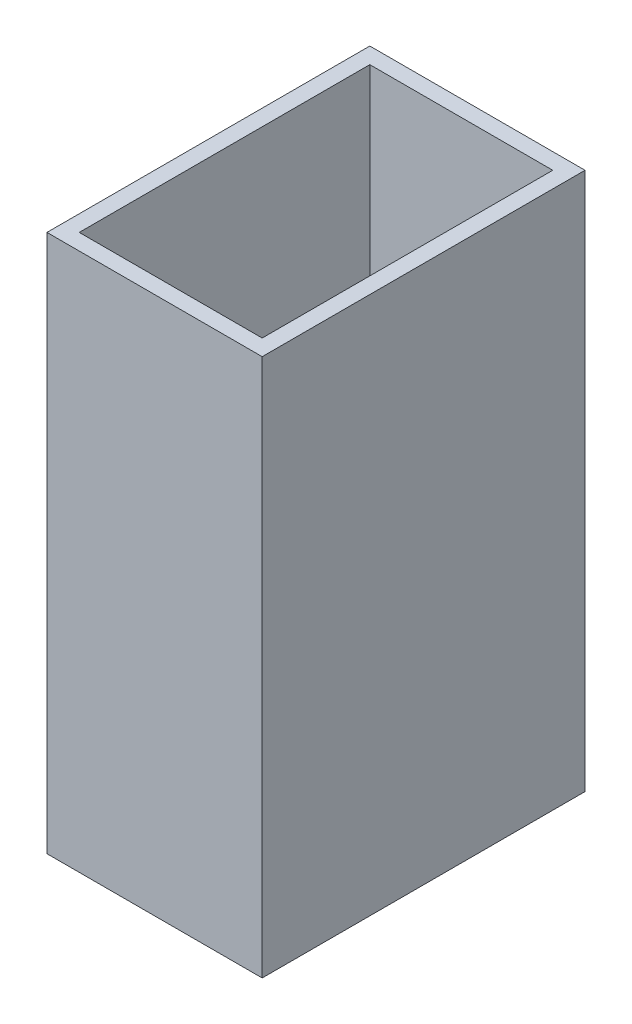
SolidWorks part; units mm, degrees
ref_plane "Front Plane" through (0, 0, 0) normal (0, 0, 1) x (1, 0, 0)
ref_plane "Top Plane" through (0, 0, 0) normal (0, 1, 0) x (1, 0, 0)
ref_plane "Right Plane" through (0, 0, 0) normal (1, 0, 0) x (0, 0, -1)
sketch "Sketch1" plane through (0, 0, 0) normal (0, 1, 0) x (1, 0, 0)
  line L1 (0, 0) -> (40, 0)
  line L2 (0, 0) -> (0, -60)
  line L3 (0, -60) -> (40, -60)
  line L4 (40, 0) -> (40, -60)
  dimension "D1" = 40
  dimension "D2" = 60
extrude "Boss-Extrude1" add sketch "Sketch1" along normal blind 100
sketch "Sketch2" plane through (0, 100, 0) normal (0, 1, 0) x (1, 0, 0)
  line L8 (3, -3) -> (3, -57)
  line L9 (3, -57) -> (37, -57)
  line L10 (37, -57) -> (37, -3)
  line L11 (37, -3) -> (3, -3)
  line L12 (3, -3) -> (3, -57)
  line L13 (3, -57) -> (37, -57)
  line L14 (37, -57) -> (37, -3)
  line L15 (37, -3) -> (3, -3)
  dimension "D1" = 3
extrude "Cut-Extrude1" cut sketch "Sketch2" against normal offset from surface 10 and the other way through all up to face at (20, 0, 30)
sketch "Sketch3" plane through (0, 0, 0) normal (0, -1, 0) x (1, 0, 0)
  line L0 (20, 60) -> (20, 0) construction
  line L1 (0, 60) -> (40, 60) construction
  line L2 (40, 0) -> (0, 0) construction
  line L3 (40, 30) -> (0, 30) construction
  line L4 (40, 60) -> (40, 0) construction
  line L5 (0, 0) -> (0, 60) construction
  circle A0 centre (7.3, 47.78) radius 2.5
  circle A1 centre (32.7, 47.78) radius 2.5
  circle A2 centre (32.7, 12.22) radius 2.5
  circle A3 centre (7.3, 12.22) radius 2.5
  dimension "D3" = 5
  dimension "D1" = 35.56
  dimension "D2" = 12.7
sketch "Sketch6" plane through (0, 10, 0) normal (0, 1, 0) x (1, 0, 0)
  point P0 (32.7, -12.22)
  point P3 (7.3, -12.22)
  point P6 (7.3, -47.78)
  point P9 (32.7, -47.78)
hole_wizard "Ø5.0 mm Dowel Holes1" positions "Sketch6" profile "Sketch5" hole size "Ø5.0" standard "ANSI Metric" end condition through all
sketch "Sketch5" plane through (32.7, 10, 12.22) normal (1, 0, 0) x (0, 0, 1)
  line L0 (0, 0) -> (0, 10)
  line L1 (0, 10) -> (2.5, 10)
  line L2 (2.5, 10) -> (2.5, 0)
  line L5 (2.5, 0) -> (0, 0)
  line L11 (0, -6.35) -> (0, 107.95) construction
  dimension "Thru Hole Dia." = 5
  dimension "Thru Hole Depth" = 10
sketch "Sketch7" plane through (0, 0, 60) normal (0, 0, 1) x (1, 0, 0)
  line L0 (20, 100) -> (20, 0) construction
  line L1 (0, 100) -> (40, 100) construction
  line L2 (0, 0) -> (40, 0) construction
